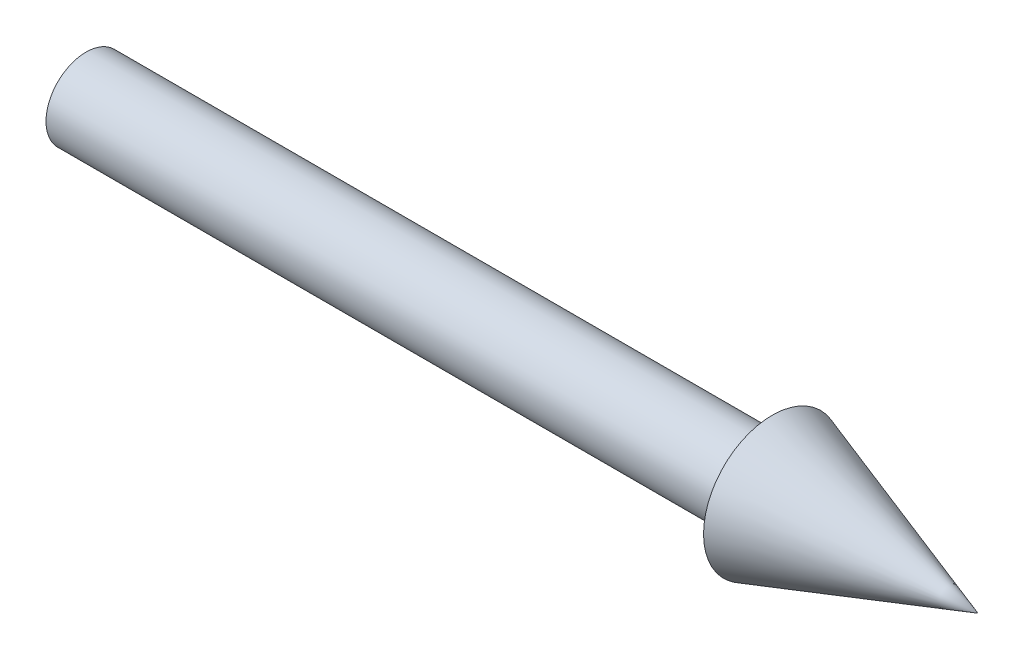
SolidWorks part; units mm, degrees
ref_plane "前视基准面" through (0, 0, 0) normal (0, 0, 1) x (1, 0, 0)
ref_plane "上视基准面" through (0, 0, 0) normal (0, 1, 0) x (1, 0, 0)
ref_plane "右视基准面" through (0, 0, 0) normal (1, 0, 0) x (0, 0, -1)
sketch "草图1" plane through (0, 0, 0) normal (0, 1, 0) x (1, 0, 0)
  line L0 (60, -6) -> (78, 0)
  line L1 (0, 0) -> (50, 0)
  line L2 (0, 0) -> (0, -3.5)
  line L3 (0, -3.5) -> (60, -3.5)
  line L5 (50, 0) -> (78, 0)
  line L6 (60, -3.5) -> (60, -6)
  dimension "D1" = 60
  dimension "D2" = 3.5
  dimension "D3" = 2.5
  dimension "D4" = 18
revolve "旋转2" add sketch "草图1" angle 360 about L1
